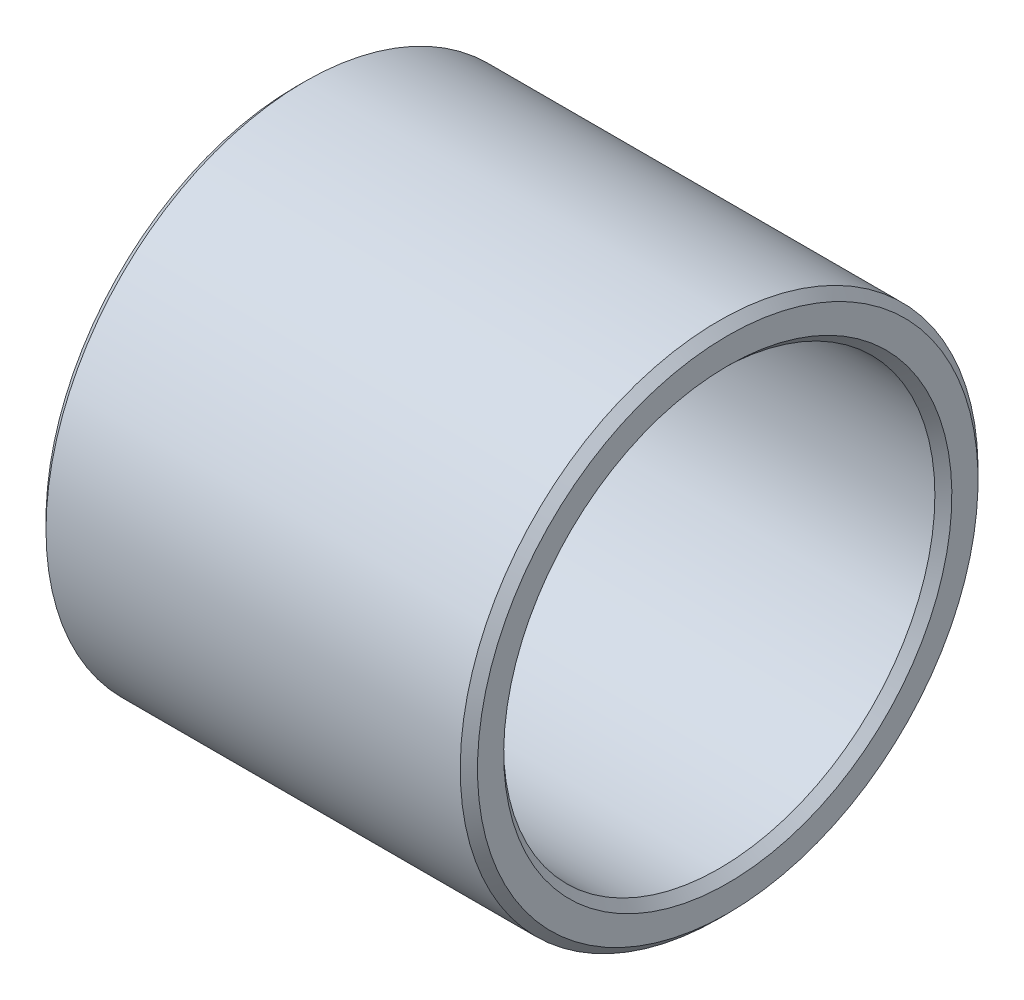
SolidWorks part; units mm, degrees
ref_plane "前视基准面" through (0, 0, 0) normal (0, 0, 1) x (1, 0, 0)
ref_plane "上视基准面" through (0, 0, 0) normal (0, 1, 0) x (1, 0, 0)
ref_plane "右视基准面" through (0, 0, 0) normal (1, 0, 0) x (0, 0, -1)
sketch "尺寸草图" plane through (0, 0, 0) normal (0, 0, 1) x (1, 0, 0)
  line L0 (-12.5, 0) -> (12.5, 0) construction
  line L1 (0, 12.5) -> (0, 0) construction
  line L2 (-12.5, 12.9828) -> (-12, 12.5)
  line L3 (-12, 12.5) -> (12, 12.5)
  line L4 (12, 12.5) -> (12.5, 12.9828)
  line L5 (-12.5, 12.9828) -> (-12.5, 14.5)
  line L6 (-12.5, 14.5) -> (-12, 15)
  line L7 (-12, 15) -> (12, 15)
  line L8 (12, 15) -> (12.5, 14.5)
  line L9 (12.5, 14.5) -> (12.5, 12.9828)
  dimension "D1" = 44
  dimension "内径d1" = 25
  dimension "倒角C1" = 0.5
  dimension "宽度b1" = 25
  dimension "倒角C2" = 0.5
  dimension "C2角度" = 45
  dimension "外径d2" = 30
revolve "旋转1" add sketch "尺寸草图" angle 360 about L0
